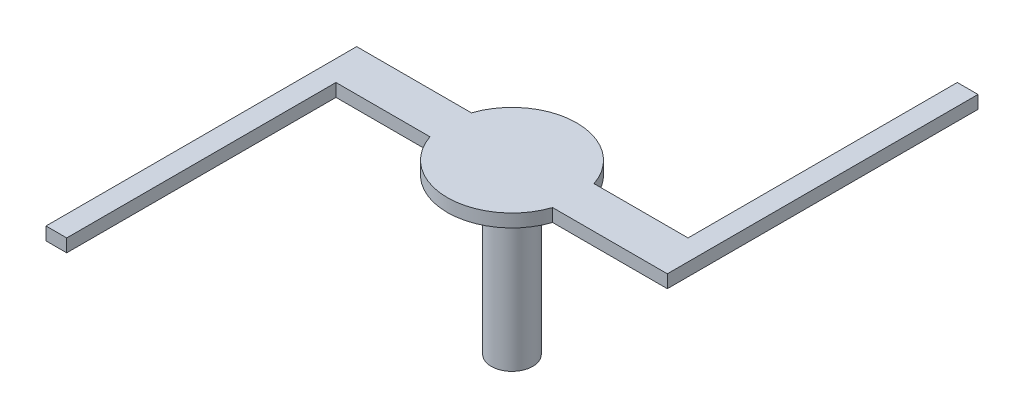
SolidWorks part; units mm, degrees
ref_plane "Спереди" through (0, 0, 0) normal (0, 0, 1) x (1, 0, 0)
ref_plane "Сверху" through (0, 0, 0) normal (0, 1, 0) x (1, 0, 0)
ref_plane "Справа" through (0, 0, 0) normal (1, 0, 0) x (0, 0, -1)
sketch "Эскиз1" plane through (0, 0, 0) normal (0, 1, 0) x (1, 0, 0)
  circle A1 centre (0, 0) radius 4
  dimension "D3" = 8
extrude "Бобышка-Вытянуть1" add sketch "Эскиз1" along normal blind 30
sketch "Эскиз2" plane through (0, 30, 0) normal (0, 1, 0) x (1, 0, 0)
  line L4 (30, 4) -> (30, 56)
  line L14 (34, -4) -> (34, 56)
  line L15 (30, 56) -> (34, 56)
  line L16 (0, 4) -> (0, -4) construction
  line L21 (-34, 4) -> (-34, -56)
  line L22 (-30, -4) -> (-30, -56)
  line L24 (-34, -56) -> (-30, -56)
  line L25 (30, 4) -> (11.8427, 4)
  line L26 (34, -4) -> (11.8427, -4)
  line L27 (-11.8427, 4) -> (-34, 4)
  line L28 (-11.8427, -4) -> (-30, -4)
  circle A4 centre (0, 0) radius 4 construction
  arc A5 (11.8427, 4) -> (-11.8427, 4) centre (0, 0) ccw
  arc A6 (-11.8427, -4) -> (11.8427, -4) centre (0, 0) ccw
  dimension "D1" = 30
  dimension "D2" = 30
  dimension "D7" = 25
  dimension "D3" = 4
  dimension "D4" = 60
  dimension "D5" = 4
  dimension "D6" = 60
extrude "Бобышка-Вытянуть2" add sketch "Эскиз2" along normal blind 2.5
